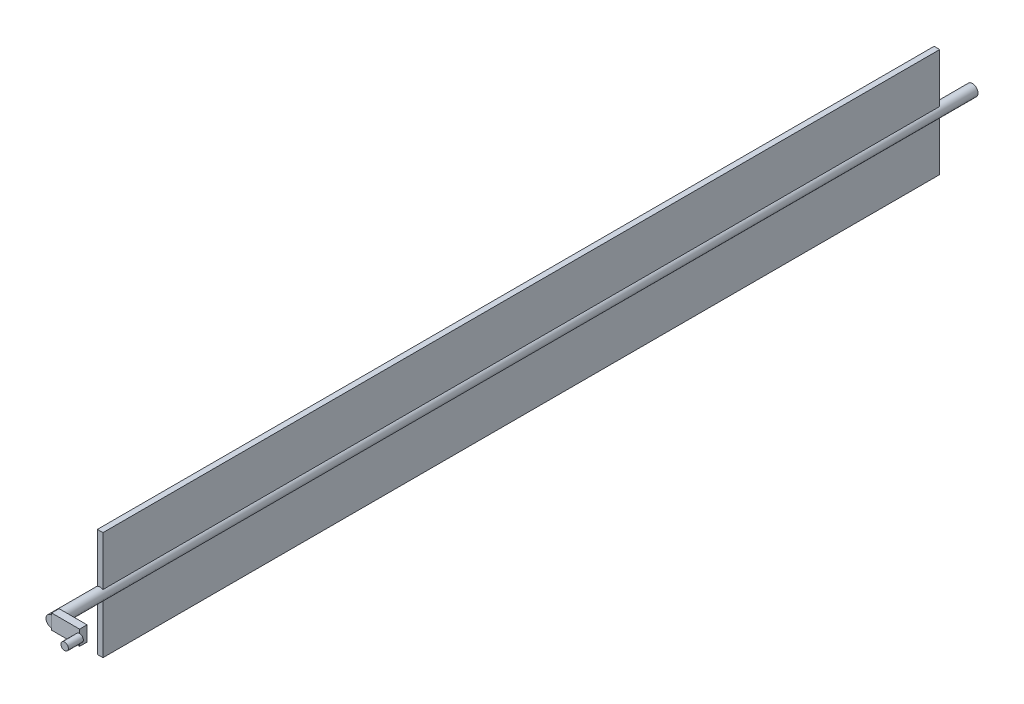
SolidWorks part; units mm, degrees
ref_plane "Front Plane" through (0, 0, 0) normal (0, 0, 1) x (1, 0, 0)
ref_plane "Top Plane" through (0, 0, 0) normal (0, 1, 0) x (1, 0, 0)
ref_plane "Right Plane" through (0, 0, 0) normal (1, 0, 0) x (0, 0, -1)
other "Configuration Table"
sketch "Sketch1" plane through (0, 0, 0) normal (1, 0, 0) x (0, 0, -1)
  line L1 (-491, -4) -> (-495, -4)
  line L2 (-491, -4) -> (-491, 4)
  line L3 (-491, 4) -> (-495, 4)
  line L4 (-495, -4) -> (-495, 4)
  line L5 (-491, -4) -> (-495, 4) construction
  line L6 (-491, 4) -> (-495, -4) construction
  point P0 (-493, 0)
extrude "crank" add sketch "Sketch1" along normal blind 15 from offset 0 separate body
sketch "Sketch2" plane through (0, 0, 0) normal (1, 0, 0) x (0, 0, -1)
  line L1 (-21, -29) -> (-469, -29)
  line L2 (-21, -29) -> (-21, 29)
  line L3 (-21, 29) -> (-469, 29)
  line L4 (-469, -29) -> (-469, 29)
  line L5 (-21, -29) -> (-469, 29) construction
  line L6 (-21, 29) -> (-469, -29) construction
  point P0 (-245, 0)
extrude "blade" add sketch "Sketch2" along normal blind 3 from offset 1.5 separate body
sketch "Sketch3" plane through (0, 0, 0) normal (0, 0, 1) x (1, 0, 0)
  circle A0 centre (0, 0) radius 3
extrude "pivot_pin" add sketch "Sketch3" along normal blind 493 from offset 2 separate body
sketch "Sketch4" plane through (0, 0, 0) normal (0, 0, 1) x (1, 0, 0)
  circle A0 centre (15, 0) radius 2
extrude "crank_pin" add sketch "Sketch4" along normal blind 8 from offset 495 separate body
